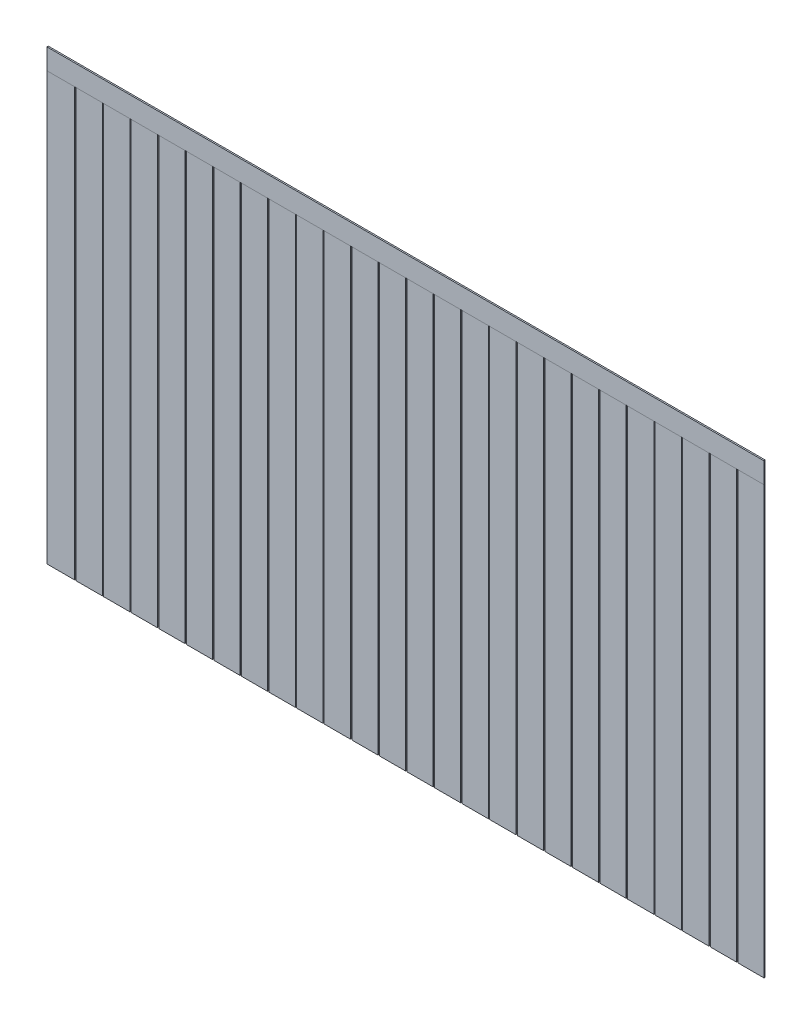
SolidWorks part; units mm, degrees
ref_plane "Alzado" through (0, 0, 0) normal (0, 0, 1) x (1, 0, 0)
ref_plane "Planta" through (0, 0, 0) normal (0, 1, 0) x (1, 0, 0)
ref_plane "Vista lateral" through (0, 0, 0) normal (1, 0, 0) x (0, 0, -1)
sketch "Croquis1" plane through (0, 0, 0) normal (0, 0, 1) x (1, 0, 0)
  line L1 (0, 0) -> (5200, 0)
  line L2 (0, 0) -> (0, -3250)
  line L3 (0, -3250) -> (5200, -3250)
  line L4 (5200, 0) -> (5200, -3250)
  dimension "D1" = 5200
  dimension "D2" = 3250
extrude "Saliente-Extruir1" add sketch "Croquis1" along normal blind 10
sketch "Croquis2" plane through (0, 0, 10) normal (0, 0, 1) x (1, 0, 0)
  line L0 (0, -3250) -> (5200, -3250) construction
  line L1 (200, -3250) -> (210, -3250)
  line L2 (200, -3250) -> (200, -150)
  line L3 (200, -150) -> (210, -150)
  line L4 (210, -3250) -> (210, -150)
  line L5 (0, 0) -> (0, -3250) construction
  line L6 (5200, 0) -> (0, 0) construction
  dimension "D1" = 200
  dimension "D2" = 150
  dimension "D3" = 10
extrude "Cortar-Extruir1" cut sketch "Croquis2" against normal blind 10
pattern_linear "MatrizL1" count 25 spacing 200 along (1, 0, 0) of "Cortar-Extruir1"
sketch "Croquis4" plane through (0, 0, 10) normal (0, 0, 1) x (1, 0, 0)
  line L0 (5200, -3250) -> (5200, 0) construction
  line L1 (0, -3250) -> (5200, -3250)
  line L2 (0, -3250) -> (0, -150)
  line L3 (0, -150) -> (5200, -150)
  line L4 (5200, -3250) -> (5200, -150)
extrude "Cortar-Extruir2" cut sketch "Croquis4" against normal blind 2
sketch "Croquis5" plane through (0, 0, 0) normal (0, 0, -1) x (-1, 0, 0)
  line L0 (0, 0) -> (0, -3250) construction
  line L1 (-5200, -3250) -> (0, -3250)
  line L2 (-5200, -3250) -> (-5200, -150)
  line L3 (-5200, -150) -> (0, -150)
  line L4 (0, -3250) -> (0, -150)
extrude "Cortar-Extruir3" cut sketch "Croquis5" against normal blind 2
